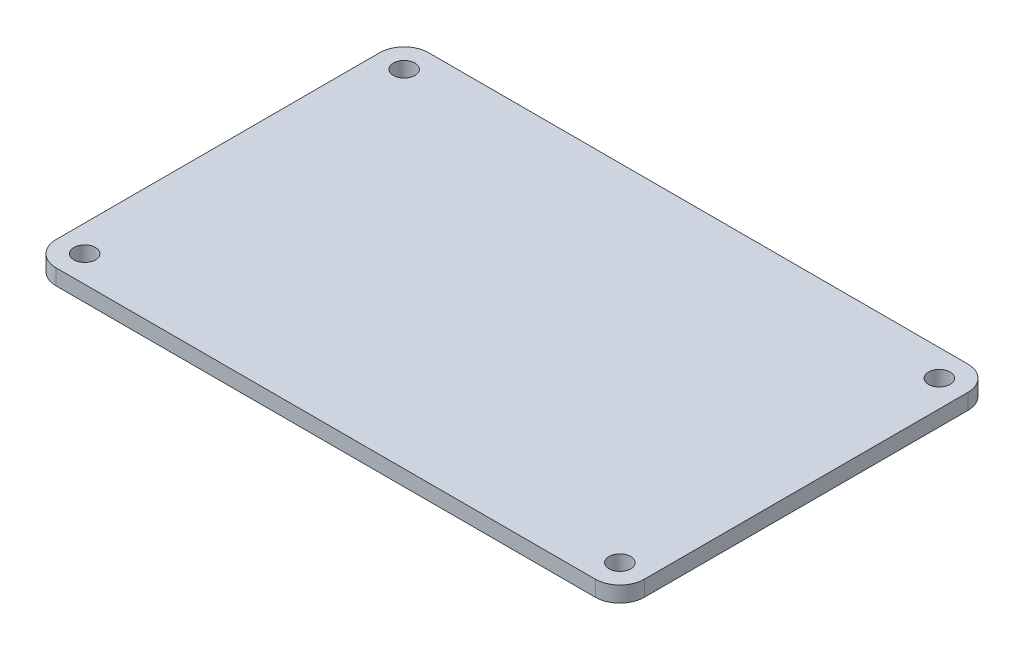
SolidWorks part; units mm, degrees
ref_plane "Front Plane" through (0, 0, 0) normal (0, 0, 1) x (1, 0, 0)
ref_plane "Top Plane" through (0, 0, 0) normal (0, 1, 0) x (1, 0, 0)
ref_plane "Right Plane" through (0, 0, 0) normal (1, 0, 0) x (0, 0, -1)
sketch "Sketch1" plane through (0, 0, 0) normal (0, 1, 0) x (1, 0, 0)
  line L0 (30, 19) -> (-30, -19) construction
  line L1 (-27.5, 19) -> (27.5, 19)
  line L2 (-30, 16.5) -> (-30, -16.5)
  line L3 (-27.5, -19) -> (27.5, -19)
  line L4 (30, 16.5) -> (30, -16.5)
  arc A0 (-27.5, 19) -> (-30, 16.5) centre (-27.5, 16.5) ccw
  arc A1 (-27.5, -19) -> (-30, -16.5) centre (-27.5, -16.5) cw
  arc A2 (27.5, -19) -> (30, -16.5) centre (27.5, -16.5) ccw
  arc A3 (27.5, 19) -> (30, 16.5) centre (27.5, 16.5) cw
  point P7 (-30, 19)
  point P13 (30, -19)
  dimension "D3" = 2.5
  dimension "D1" = 60
  dimension "D2" = 38
extrude "Boss-Extrude1" add sketch "Sketch1" along normal blind 1.6
sketch "Sketch2" plane through (0, 1.6, 0) normal (0, 1, 0) x (1, 0, 0)
  line L0 (-6.3217, 0) -> (6.5388, 0) construction
  line L1 (0, 4.9082) -> (0, -5.5647) construction
  circle A0 centre (-27.29, 16.29) radius 1.1
  circle A1 centre (27.29, 16.29) radius 1.1
  circle A2 centre (27.29, -16.29) radius 1.1
  circle A3 centre (-27.29, -16.29) radius 1.1
  point P13 (0, 0)
  point P14 (0, 0)
  point P15 (0, 0)
  point P16 (0, 0)
  point P17 (0, 0)
  point P18 (0, 0)
  dimension "D3" = 2.2
  dimension "D1" = 32.58
  dimension "D2" = 54.58
extrude "Cut-Extrude1" cut sketch "Sketch2" against normal through all
